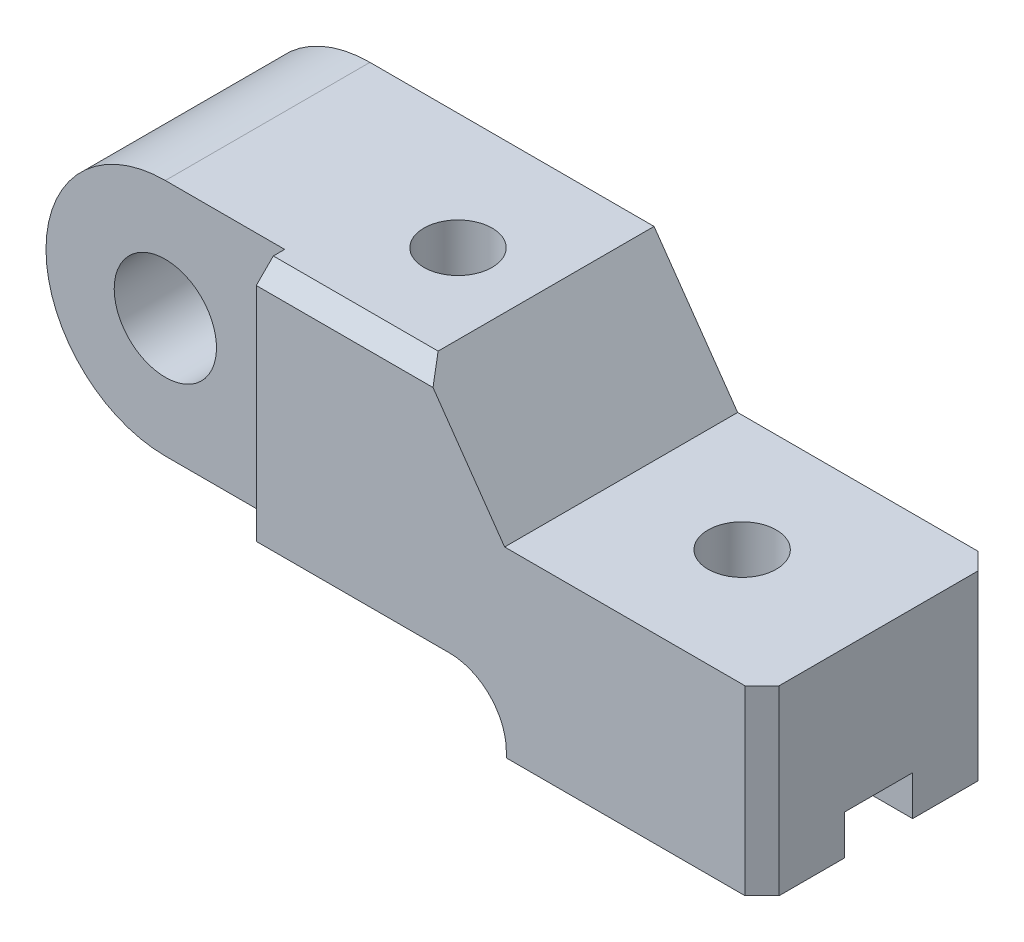
SolidWorks part; units mm, degrees
ref_plane "Front Plane" through (0, 0, 0) normal (0, 0, 1) x (1, 0, 0)
ref_plane "Top Plane" through (0, 0, 0) normal (0, 1, 0) x (1, 0, 0)
ref_plane "Right Plane" through (0, 0, 0) normal (1, 0, 0) x (0, 0, -1)
sketch "Sketch1" plane through (0, 0, 0) normal (0, 0, 1) x (1, 0, 0)
  line L0 (0, 21) -> (50, 21)
  line L1 (50, 21) -> (64.7044, 0)
  line L2 (64.7044, 0) -> (110, 0)
  line L3 (110, 0) -> (110, -32)
  line L4 (110, -32) -> (65, -32)
  line L5 (65, -32) -> (65, -31)
  line L6 (55, -21) -> (0, -21)
  circle A0 centre (0, 0) radius 9
  circle A1 centre (0, 0) radius 21
  arc A2 (65, -31) -> (55, -21) centre (55, -31) ccw
  dimension "D1" = 42
  dimension "D2" = 18
  dimension "D6" = 10
  dimension "D3" = 110
  dimension "D4" = 45
  dimension "D5" = 32
  dimension "D7" = 55
  dimension "D8" = 50
extrude "Boss-Extrude1" add sketch "Sketch1" along normal mid plane 41 contours A2 L5 L4 L3 L2 L1 L0 A1 L6 | A1 A0
sketch "Sketch2" plane through (0, 21, 0) normal (0, 1, 0) x (1, 0, 0)
  line L0 (-28.9798, 0) -> (115.9598, 0) construction
  line L1 (-21, 20.5) -> (-21, -20.5) construction
  line L2 (-21, -15.5) -> (21, -15.5)
  line L3 (-21, -15.5) -> (-21, -20.5)
  line L4 (-21, -20.5) -> (21, -20.5)
  line L5 (21, -15.5) -> (21, -20.5)
  line L6 (0, -20.5) -> (50, -20.5) construction
  circle A0 centre (36, 0) radius 6
  circle A1 centre (86, 0) radius 6
  point P17 (31.8746, -36.2601)
  dimension "D3" = 12
  dimension "D4" = 12
  dimension "D1" = 5
  dimension "D2" = 42
  dimension "D5" = 50
  dimension "D6" = 15
extrude "Cut-Extrude1" cut sketch "Sketch2" against normal blind 55
sketch "Sketch3" plane through (110, 0, 0) normal (1, 0, 0) x (0, 0, -1)
  line L0 (-20.5, -32) -> (20.5, -32) construction
  line L1 (-6, -32) -> (6, -32)
  line L2 (-6, -32) -> (-6, -25)
  line L3 (-6, -25) -> (6, -25)
  line L4 (6, -32) -> (6, -25)
  line L5 (0, -3.7372) -> (0, 2.8731) construction
  dimension "D1" = 12
  dimension "D2" = 7
extrude "Cut-Extrude2" cut sketch "Sketch3" against normal blind 55
chamfer "Chamfer1" distance 3 angle 45 3 edges at (35.5, 21, 20.5) (110, -16, -20.5) (110, -16, 20.5)
